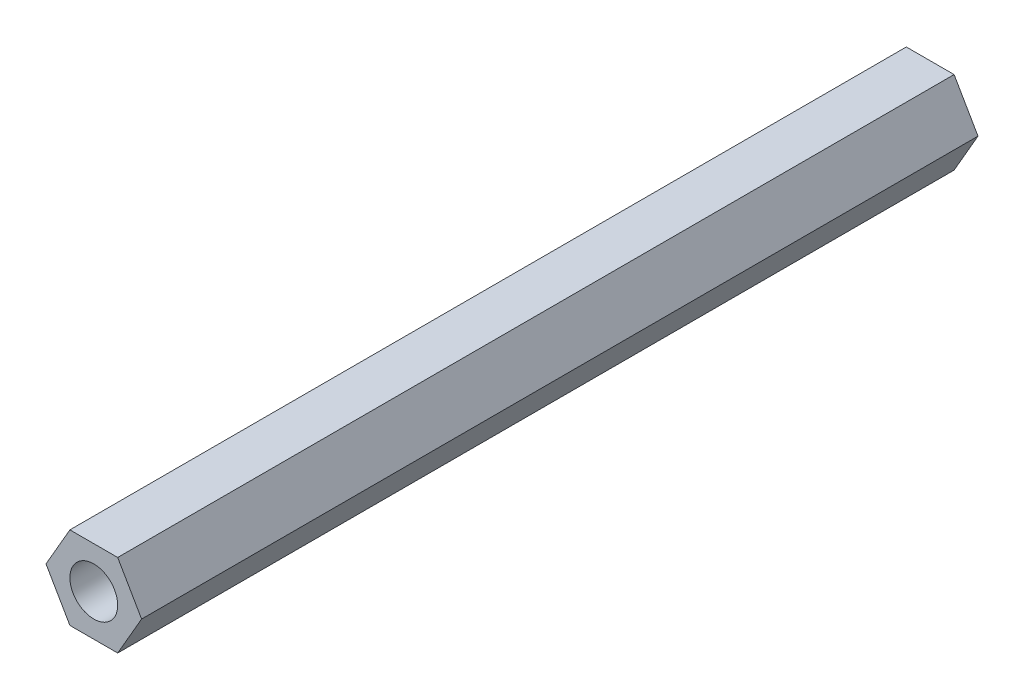
SolidWorks part; units mm, degrees
ref_plane "前视基准面" through (0, 0, 0) normal (0, 0, 1) x (1, 0, 0)
ref_plane "上视基准面" through (0, 0, 0) normal (0, 1, 0) x (1, 0, 0)
ref_plane "右视基准面" through (0, 0, 0) normal (1, 0, 0) x (0, 0, -1)
sketch "草图1" plane through (0, 0, 0) normal (0, 0, 1) x (1, 0, 0)
  line L1 (19.2583, 75.5773) -> (17.2583, 79.0414)
  line L2 (17.2583, 79.0414) -> (13.2583, 79.0414)
  line L3 (13.2583, 79.0414) -> (11.2583, 75.5773)
  line L4 (11.2583, 75.5773) -> (13.2583, 72.1132)
  line L5 (13.2583, 72.1132) -> (17.2583, 72.1132)
  line L6 (17.2583, 72.1132) -> (19.2583, 75.5773)
  circle A0 centre (15.2583, 75.5773) radius 3.4641 construction
  circle A1 centre (15.2583, 75.5773) radius 2
  dimension "D1" = 4
  dimension "D2" = 4
extrude "凸台-拉伸1" add sketch "草图1" along normal blind 70
